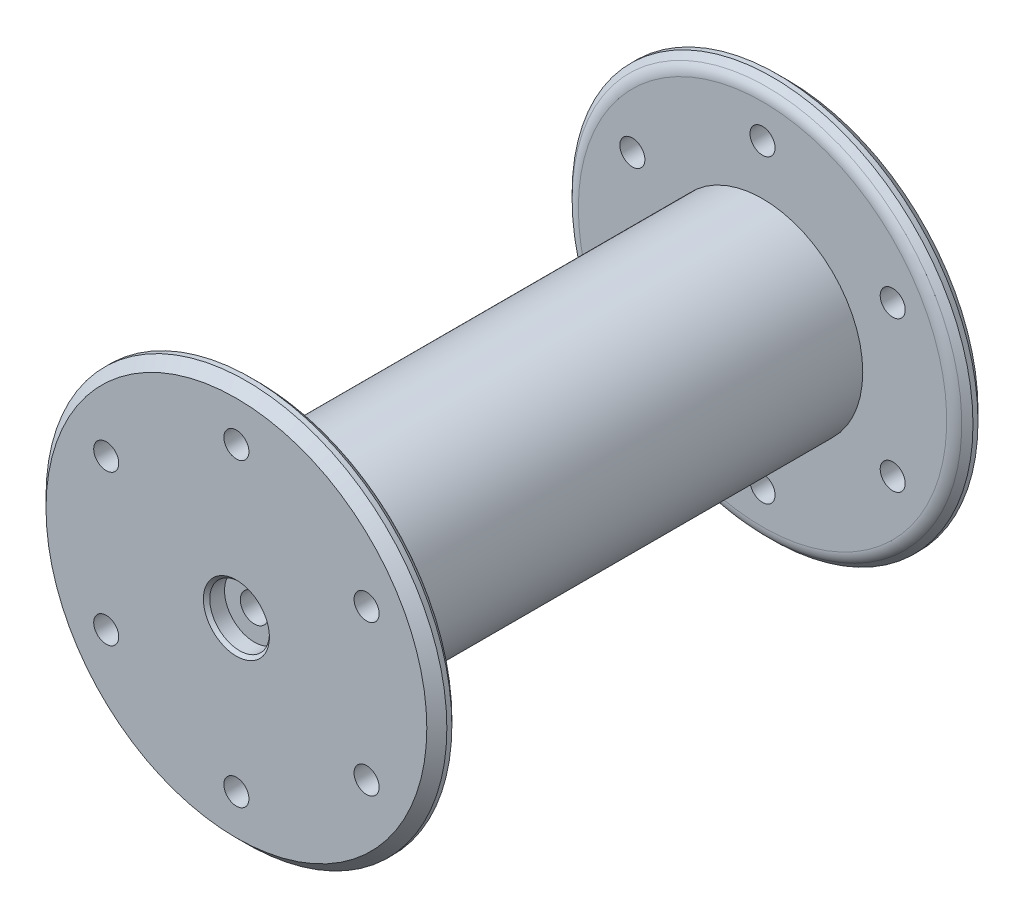
SolidWorks part; units mm, degrees
ref_plane "Front Plane" through (0, 0, 0) normal (0, 0, 1) x (1, 0, 0)
ref_plane "Top Plane" through (0, 0, 0) normal (0, 1, 0) x (1, 0, 0)
ref_plane "Right Plane" through (0, 0, 0) normal (1, 0, 0) x (0, 0, -1)
sketch "Sketch1" plane through (0, 0, 0) normal (0, 0, 1) x (1, 0, 0)
  circle A0 centre (0, 0) radius 20
  dimension "ShaftDiameter" = 40
extrude "Boss-Extrude1" add sketch "Sketch1" along normal mid plane 100
sketch "Sketch3" plane through (0, 0, 50) normal (0, 0, 1) x (1, 0, 0)
  circle A0 centre (0, 0) radius 40
  dimension "CapDiameter" = 80
extrude "Boss-Extrude2" add sketch "Sketch3" along normal blind 5
chamfer "Chamfer1" distance 2 angle 45 2 edges at (40, 0, 50) (40, 0, 55)
sketch "Sketch5" plane through (0, 0, 55) normal (0, 0, 1) x (1, 0, 0)
  line L0 (0, 40) -> (0, 20) construction
  circle A0 centre (0, 0) radius 40 construction
  circle A1 centre (0, 0) radius 20 construction
  circle A2 centre (0, 30) radius 2.5
  dimension "D1" = 5
extrude "Cut-Extrude1" cut sketch "Sketch5" against normal through all contours A2
pattern_circular "CirPattern1" count 6 over 360 about axis through (0, 0, 0) along (0, 0, 1) of "Cut-Extrude1"
fillet "Fillet2" radius 3 1 edges at (38, 0, 50)
hole_wizard "CBORE for #12 Binding Head Machine Screw1" positions "Sketch7" profile "Sketch8" counterbore size "#12" standard "ANSI Inch" end condition through all
sketch "Sketch7" plane through (0, 0, 55) normal (0, 0, 1) x (1, 0, 0)
  point P0 (0, 0)
sketch "Sketch8" plane through (0, 0, 55) normal (1, 0, 0) x (0, -1, 0)
  line L0 (0, 0) -> (0, 110)
  line L1 (0, 110) -> (2.8067, 110)
  line L3 (2.8067, 110) -> (2.8067, 3.5814)
  line L4 (5.9538, 3.5814) -> (2.8067, 3.5814)
  line L5 (5.9538, 3.5814) -> (5.9538, 0.635)
  line L6 (5.9538, 0.635) -> (6.5888, 0)
  line L7 (6.5888, 0) -> (0, 0)
  line L8 (-5.9538, 0.635) -> (-6.5888, 0) construction
  line L11 (0, -6.35) -> (0, 107.95) construction
  dimension "Thru Hole Dia." = 5.6134
  dimension "Thru Hole Depth" = 110
  dimension "C'Bore Dia." = 11.9075
  dimension "C'Bore Depth" = 3.5814
  dimension "Near C'Sink Dia." = 13.1775
  dimension "Near C'Sink Angle" = 90
mirror "Mirror3" about plane through (0, 0, 0) normal (0, 0, 1) of "CBORE for #12 Binding Head Machine Screw1", "Fillet2", "CirPattern1", "Cut-Extrude1", "Chamfer1", "Boss-Extrude2", "Boss-Extrude1"
